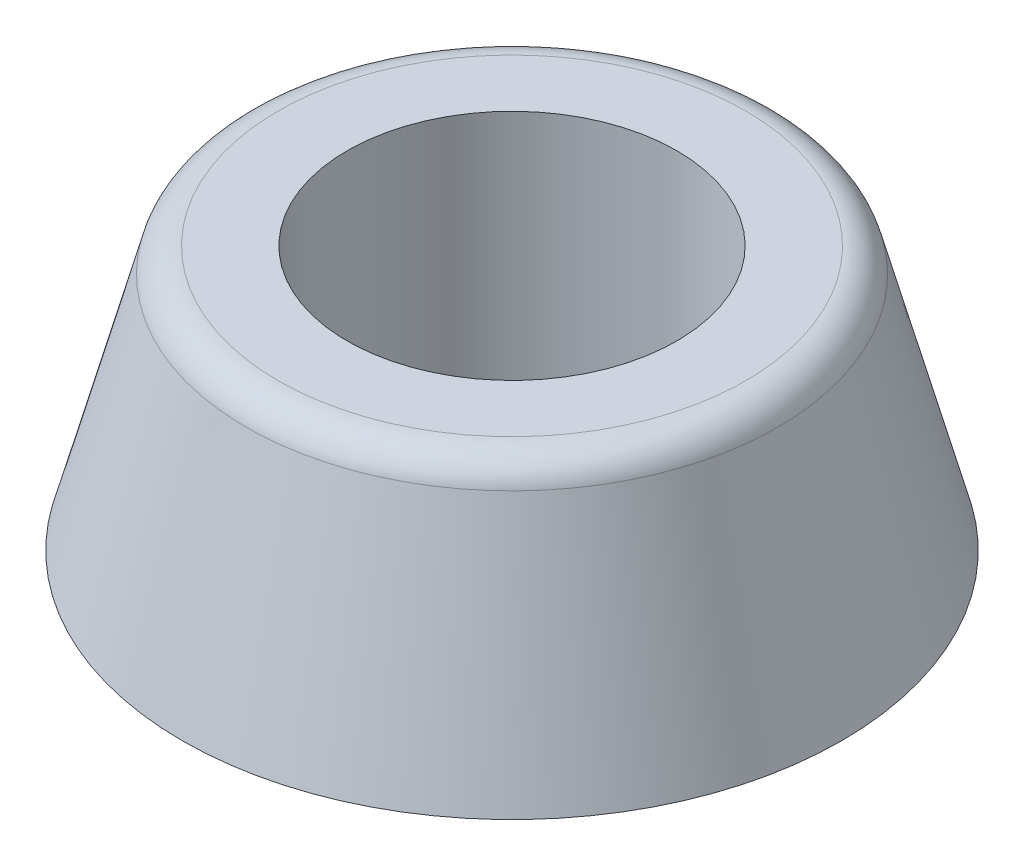
SolidWorks part; units mm, degrees
ref_plane "Front Plane" through (0, 0, 0) normal (0, 0, 1) x (1, 0, 0)
ref_plane "Top Plane" through (0, 0, 0) normal (0, 1, 0) x (1, 0, 0)
ref_plane "Right Plane" through (0, 0, 0) normal (1, 0, 0) x (0, 0, -1)
sketch "Sketch1" plane through (0, 0, 0) normal (0, 0, 1) x (1, 0, 0)
  line L0 (0, -21.8657) -> (0, 48.9375) construction
  line L1 (5, 4) -> (10, 4)
  line L2 (10, 4) -> (8.055, 11.2588)
  line L3 (7.0891, 12) -> (5, 12)
  line L5 (5, 4) -> (5, 12)
  arc A0 (7.0891, 12) -> (8.055, 11.2588) centre (7.0891, 11) cw
  point P9 (7.8564, 12)
  dimension "D4" = 1
  dimension "D1" = 5
  dimension "D2" = 8
  dimension "D3" = 75
  dimension "D5" = 10
revolve "Revolve1" add sketch "Sketch1" angle 360 about L0
